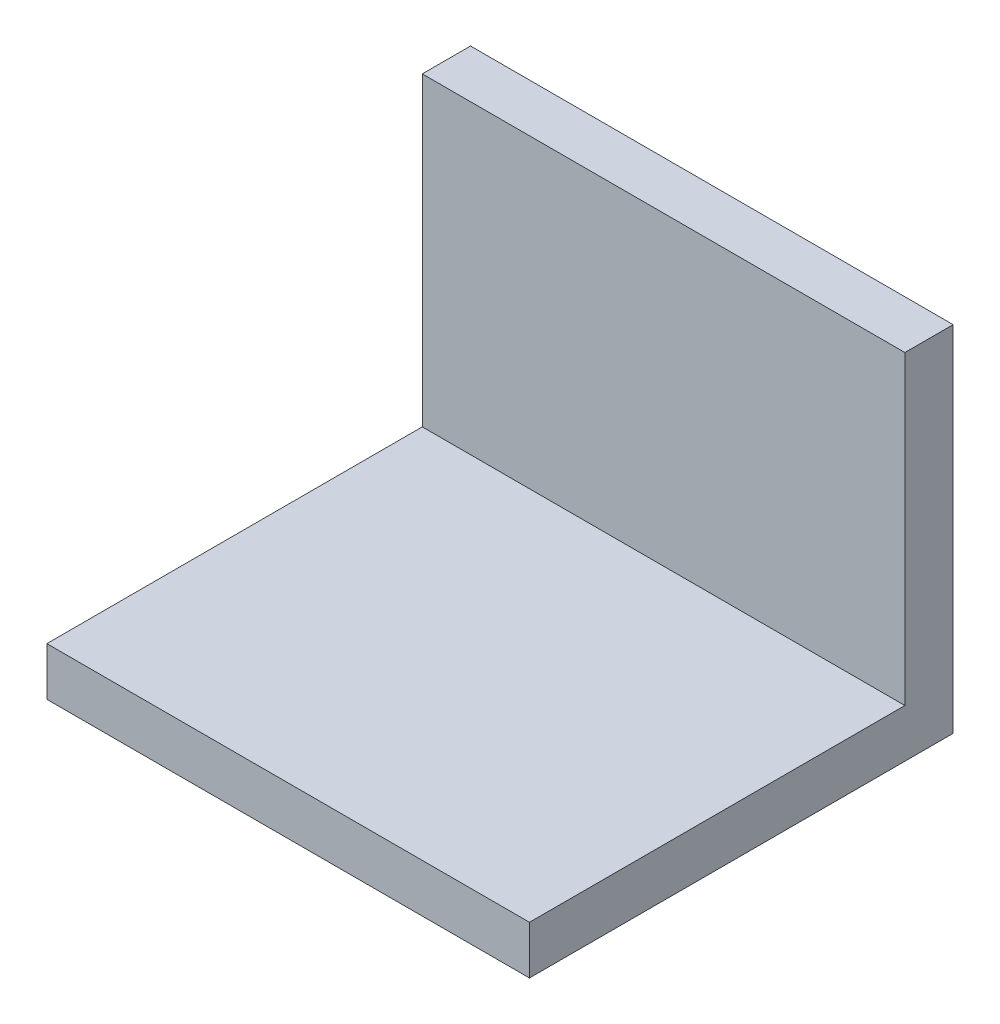
SolidWorks part; units mm, degrees
ref_plane "Front Plane" through (0, 0, 0) normal (0, 0, 1) x (1, 0, 0)
ref_plane "Top Plane" through (0, 0, 0) normal (0, 1, 0) x (1, 0, 0)
ref_plane "Right Plane" through (0, 0, 0) normal (1, 0, 0) x (0, 0, -1)
sketch "Sketch1" plane through (0, 0, 0) normal (1, 0, 0) x (0, 0, -1)
  line L0 (0, 0) -> (66.894, 0)
  line L1 (66.894, 0) -> (66.894, 55.8859)
  line L2 (66.894, 55.8859) -> (59.274, 55.8859)
  line L3 (59.274, 55.8859) -> (59.274, 7.62)
  line L4 (59.274, 7.62) -> (0, 7.62)
  line L5 (0, 7.62) -> (0, 0)
extrude "Extrude1" add sketch "Sketch1" against normal blind 76.2
ref_plane "Plane1" through (-38.1, 0, 0) normal (1, 0, 0) x (0, 0, -1)
